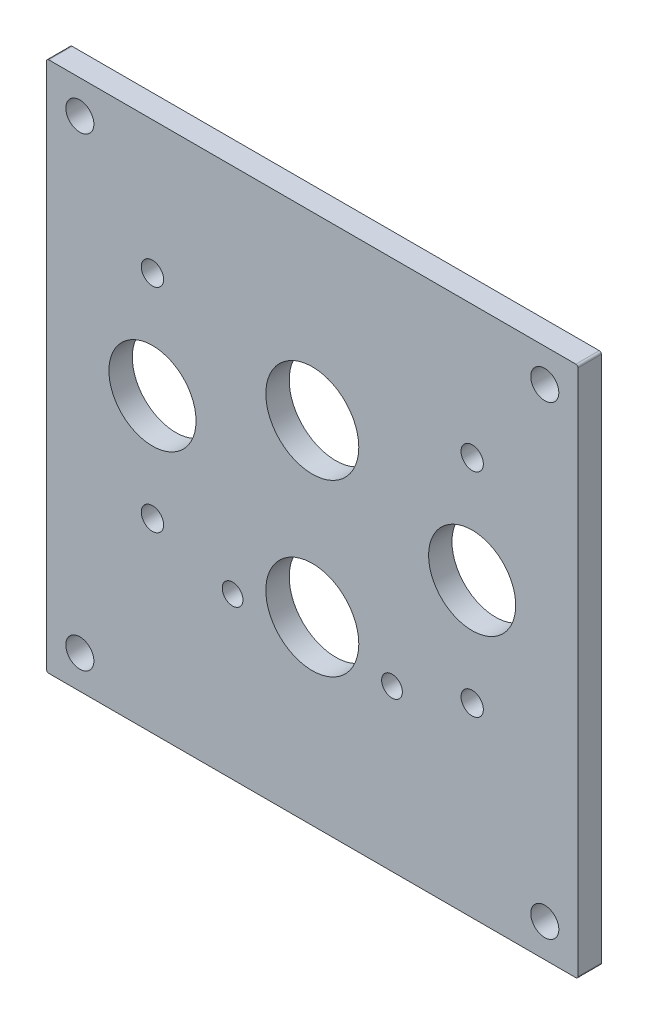
SolidWorks part; units mm, degrees
material "6061 Alloy"
ref_plane "Front Plane" through (0, 0, 0) normal (0, 0, 1) x (1, 0, 0)
ref_plane "Top Plane" through (0, 0, 0) normal (0, 1, 0) x (1, 0, 0)
ref_plane "Right Plane" through (0, 0, 0) normal (1, 0, 0) x (0, 0, -1)
sketch "Sketch1" plane through (0, 0, 0) normal (0, 0, 1) x (1, 0, 0)
  line L2 (-63.5, -63.5) -> (0, -63.5)
  line L3 (0, 63.5) -> (0, -63.5)
  line L9 (-63.5, 63.5) -> (-63.5, -63.5)
  line L10 (0, 63.5) -> (-63.5, 63.5)
  dimension "D1" = 63.5
  dimension "D2" = 127
extrude "Extrude1" add sketch "Sketch1" along normal mid plane 5.59
sketch "Sketch2" plane through (0, 0, 2.795) normal (0, 0, 1) x (1, 0, 0)
  line L0 (0, 63.5) -> (0, -63.5) construction
  line L1 (-63.5, 63.5) -> (-63.5, -63.5) construction
  line L2 (0, 63.5) -> (-63.5, 63.5) construction
  line L3 (0, 0) -> (-63.5, 0) construction
  line L4 (0, 0) -> (0, 97.0716) construction
  circle A0 centre (-55.5625, 55.5625) radius 3.3528
  circle A1 centre (-38.2016, 6.35) radius 10.414
  circle A2 centre (-38.2083, -19.05) radius 2.667
  circle A3 centre (-19.05, -25.1079) radius 2.4765
  circle A4 centre (-38.2083, 31.75) radius 2.667
  circle A5 centre (0, -20.3454) radius 11.1125
  circle A6 centre (-55.5625, -55.5625) radius 3.3528
  circle A8 centre (0, 20.3454) radius 11.1125
  point P1 (0, 0)
  dimension "D2" = 22.225
  dimension "D5" = 6.7056
  dimension "D6" = 20.828
  dimension "D9" = 4.953
  dimension "D10" = 5.334
  dimension "D11" = 38.1
  dimension "D1" = 20.3454
  dimension "D3" = 7.9375
  dimension "D4" = 7.9375
  dimension "D7" = 38.2016
  dimension "D8" = 6.35
  dimension "D12" = 25.1079
  dimension "D13" = 19.05
  dimension "D14" = 38.2083
  dimension "D15" = 31.75
extrude "Extrude2" cut sketch "Sketch2" against normal through all
fillet "Fillet1" radius 0.508 2 edges at (-63.5, -63.5, 0) (-63.5, 63.5, 0)
mirror "Mirror1" about plane through (0, -110.584, 2.795) normal (1, 0, 0) of bodies 104
